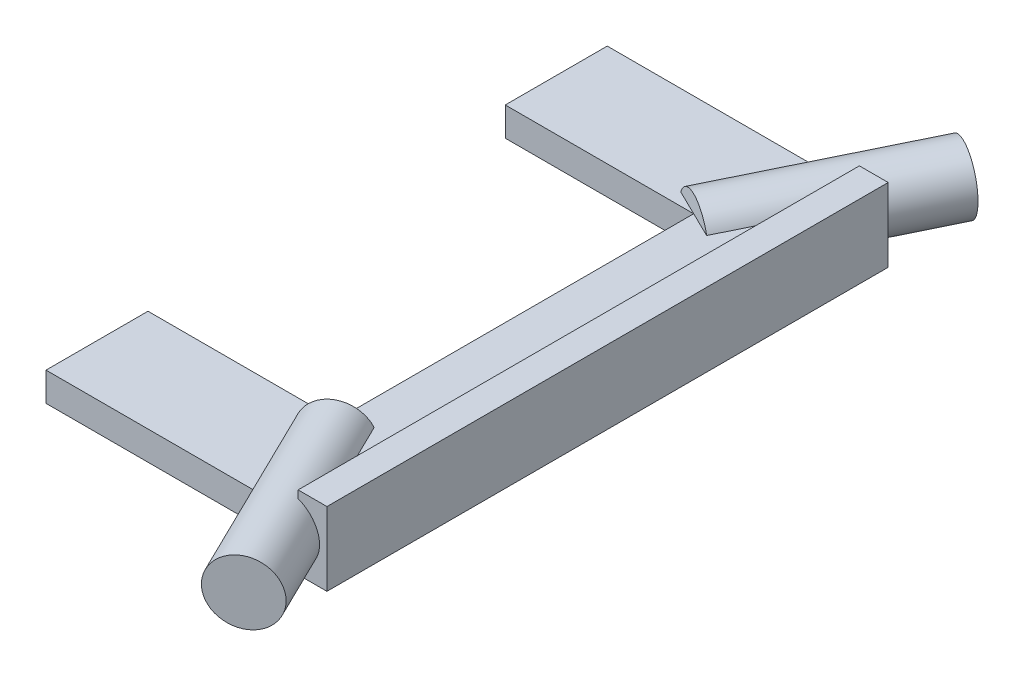
SolidWorks part; units mm, degrees
ref_plane "Front Plane" through (0, 0, 0) normal (0, 0, 1) x (1, 0, 0)
ref_plane "Top Plane" through (0, 0, 0) normal (0, 1, 0) x (1, 0, 0)
ref_plane "Right Plane" through (0, 0, 0) normal (1, 0, 0) x (0, 0, -1)
sketch "Sketch1" plane through (0, 0, 0) normal (0, 1, 0) x (1, 0, 0)
  line L1 (-36.055, -48.7) -> (36.055, -48.7)
  line L2 (-36.055, -48.7) -> (-36.055, 48.7)
  line L3 (-36.055, 48.7) -> (36.055, 48.7)
  line L4 (36.055, -48.7) -> (36.055, 48.7)
  line L5 (-36.055, -48.7) -> (36.055, 48.7) construction
  line L6 (-36.055, 48.7) -> (36.055, -48.7) construction
  point P0 (0, 0)
  dimension "D1" = 72.11
  dimension "D2" = 97.4
extrude "Boss-Extrude1" add sketch "Sketch1" along normal mid plane 5
sketch "Sketch2" plane through (0, 0, 0) normal (0, 1, 0) x (1, 0, 0)
  line L0 (-36.055, -48.7) -> (36.055, -48.7) construction
  line L1 (-36.055, 48.7) -> (-31.055, 48.7)
  line L2 (-36.055, 48.7) -> (-36.055, -48.7)
  line L3 (-36.055, -48.7) -> (-31.055, -48.7)
  line L4 (-31.055, 48.7) -> (-31.055, -48.7)
  line L6 (36.055, 48.7) -> (31.055, 48.7)
  line L7 (36.055, 48.7) -> (36.055, -48.7)
  line L8 (36.055, -48.7) -> (31.055, -48.7)
  line L9 (31.055, 48.7) -> (31.055, -48.7)
  dimension "D1" = 5
extrude "Boss-Extrude2" add sketch "Sketch2" along normal mid plane 12.75
sketch "Sketch3" plane through (0, 2.5, 0) normal (0, 1, 0) x (1, 0, 0)
  line L5 (-20, -31) -> (20, -31)
  line L6 (-20, -31) -> (-20, 31)
  line L7 (-20, 31) -> (20, 31)
  line L8 (20, -31) -> (20, 31)
  line L9 (-20, -31) -> (20, 31) construction
  line L10 (-20, 31) -> (20, -31) construction
  point P0 (0, 0)
  dimension "D1" = 40
  dimension "D2" = 62
extrude "Cut-Extrude1" cut sketch "Sketch3" against normal through all both and the other way through all
sketch "Sketch4" plane through (0, 0, 0) normal (0, 1, 0) x (1, 0, 0)
  line L0 (20, 31) -> (28.6492, 48.7) construction
  line L1 (31.055, 48.7) -> (-31.055, 48.7) construction
  line L2 (20, 31) -> (15.0584, 33.4147)
  line L3 (15.0584, 33.4147) -> (30.4249, 64.8611)
  line L4 (30.4249, 64.8611) -> (35.3664, 62.4464)
  line L5 (35.3664, 62.4464) -> (20, 31)
  dimension "D1" = 5.5
  dimension "D2" = 35
revolve "Revolve1" add sketch "Sketch4" angle 360 about L0
mirror "Mirror1" about plane through (0, 0, 0) normal (0, 0, 1) of "Revolve1"
sketch "Sketch5" plane through (0, 0, 0) normal (0, 1, 0) x (1, 0, 0)
  line L1 (-44.45, 76.2) -> (-12.7, 76.2)
  line L2 (-44.45, 76.2) -> (-44.45, -76.2)
  line L3 (-44.45, -76.2) -> (-12.7, -76.2)
  line L4 (-12.7, 76.2) -> (-12.7, -76.2)
  point P4 (-44.45, 0)
  dimension "D1" = 152.4
  dimension "D2" = 12.7
  dimension "D3" = 31.75
extrude "Cut-Extrude2" cut sketch "Sketch5" against normal through all both and the other way through all
